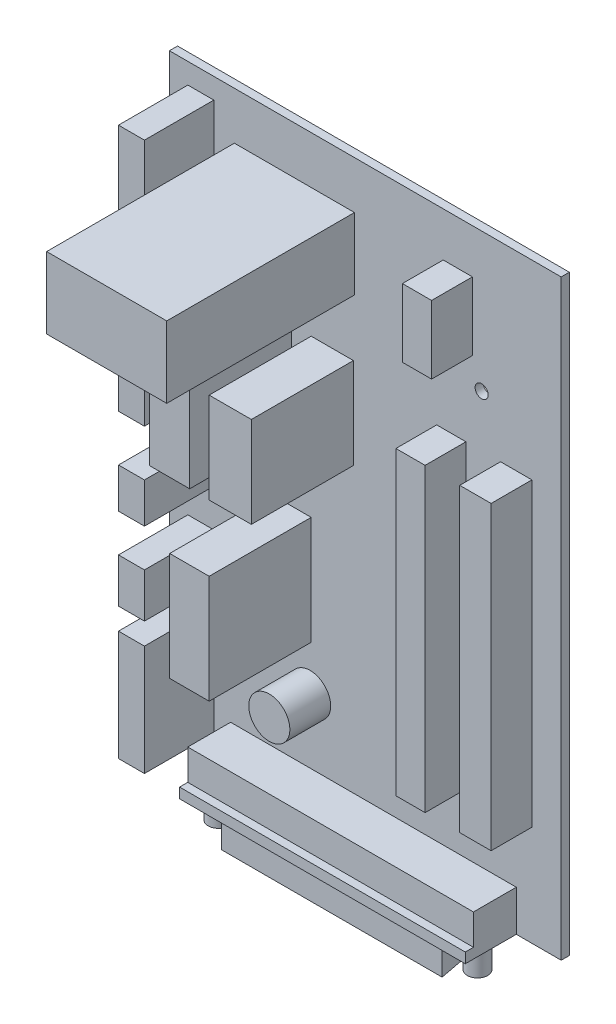
SolidWorks part; units mm, degrees
ref_plane "前视基准面" through (0, 0, 0) normal (0, 0, 1) x (1, 0, 0)
ref_plane "上视基准面" through (0, 0, 0) normal (0, 1, 0) x (1, 0, 0)
ref_plane "右视基准面" through (0, 0, 0) normal (1, 0, 0) x (0, 0, -1)
sketch "草图1" plane through (0, 0, 0) normal (0, 0, 1) x (1, 0, 0)
  line L0 (0, 0) -> (0, 68.734) construction
  line L1 (-48, 72.5) -> (48, 72.5)
  line L2 (-48, 72.5) -> (-48, -72.5)
  line L3 (-48, -72.5) -> (48, -72.5)
  line L4 (48, 72.5) -> (48, -72.5)
  line L5 (0, 0) -> (52.2466, 0) construction
  dimension "D1" = 96
  dimension "D2" = 145
extrude "凸台-拉伸1" add sketch "草图1" along normal blind 2
sketch "草图2" plane through (0, 0, 2) normal (0, 0, 1) x (1, 0, 0)
  line L1 (-43.4773, 67.4693) -> (-37.1147, 67.4693)
  line L2 (-43.4773, 67.4693) -> (-43.4773, 38.0426)
  line L3 (-43.4773, 38.0426) -> (-37.1147, 38.0426)
  line L4 (-37.1147, 67.4693) -> (-37.1147, 38.0426)
  line L5 (-43.4773, 29.5592) -> (-37.1147, 29.5592)
  line L6 (-43.4773, 29.5592) -> (-43.4773, 6.7602)
  line L7 (-43.4773, 6.7602) -> (-37.1147, 6.7602)
  line L8 (-37.1147, 29.5592) -> (-37.1147, 6.7602)
  line L9 (-43.4773, -4.6393) -> (-37.1147, -4.6393)
  line L10 (-43.4773, -4.6393) -> (-43.4773, -14.4482)
  line L11 (-43.4773, -14.4482) -> (-37.1147, -14.4482)
  line L12 (-37.1147, -4.6393) -> (-37.1147, -14.4482)
  line L13 (-43.4773, -23.7269) -> (-37.1147, -23.7269)
  line L14 (-43.4773, -23.7269) -> (-43.4773, -34.5962)
  line L15 (-43.4773, -34.5962) -> (-37.1147, -34.5962)
  line L16 (-37.1147, -23.7269) -> (-37.1147, -34.5962)
  line L17 (-43.4773, -39.8983) -> (-37.1147, -39.8983)
  line L18 (-43.4773, -39.8983) -> (-43.4773, -66.9391)
  line L19 (-43.4773, -66.9391) -> (-37.1147, -66.9391)
  line L20 (-37.1147, -39.8983) -> (-37.1147, -66.9391)
extrude "凸台-拉伸2" add sketch "草图2" along normal blind 17
sketch "草图3" plane through (0, 0, 2) normal (0, 0, 1) x (1, 0, 0)
  line L1 (-32.0777, 60.8417) -> (-2.6511, 60.8417)
  line L2 (-32.0777, 60.8417) -> (-32.0777, 43.3447)
  line L3 (-32.0777, 43.3447) -> (-2.6511, 43.3447)
  line L4 (-2.6511, 60.8417) -> (-2.6511, 43.3447)
extrude "凸台-拉伸3" add sketch "草图3" along normal blind 46
sketch "草图4" plane through (0, 0, 2) normal (0, 0, 1) x (1, 0, 0)
  line L1 (-27.8361, 29.2941) -> (-18.0272, 29.2941)
  line L2 (-27.8361, 29.2941) -> (-27.8361, 7.0253)
  line L3 (-27.8361, 7.0253) -> (-18.0272, 7.0253)
  line L4 (-18.0272, 29.2941) -> (-18.0272, 7.0253)
  line L5 (-13.2553, 29.2941) -> (-2.9162, 29.2941)
  line L6 (-13.2553, 29.2941) -> (-13.2553, 7.0253)
  line L7 (-13.2553, 7.0253) -> (-2.9162, 7.0253)
  line L8 (-2.9162, 29.2941) -> (-2.9162, 7.0253)
  line L9 (-22.9316, -9.1461) -> (-13.2553, -9.1461)
  line L10 (-22.9316, -9.1461) -> (-22.9316, -35.6567)
  line L11 (-22.9316, -35.6567) -> (-13.2553, -35.6567)
  line L12 (-13.2553, -9.1461) -> (-13.2553, -35.6567)
extrude "凸台-拉伸4" add sketch "草图4" along normal blind 25
sketch "草图5" plane through (0, 0, 2) normal (0, 0, 1) x (1, 0, 0)
  circle A0 centre (-13.5204, -46.7911) radius 5.037
extrude "凸台-拉伸5" add sketch "草图5" along normal blind 10
sketch "草图6" plane through (0, 0, 2) normal (0, 0, 1) x (1, 0, 0)
  line L1 (19.0876, 61.637) -> (26.2454, 61.637)
  line L2 (19.0876, 61.637) -> (19.0876, 44.9353)
  line L3 (19.0876, 44.9353) -> (26.2454, 44.9353)
  line L4 (26.2454, 61.637) -> (26.2454, 44.9353)
extrude "凸台-拉伸6" add sketch "草图6" along normal blind 10
sketch "草图7" plane through (0, 0, 2) normal (0, 0, 1) x (1, 0, 0)
  line L1 (17.4969, 25.8478) -> (24.6548, 25.8478)
  line L2 (17.4969, 25.8478) -> (17.4969, -47.8515)
  line L3 (17.4969, -47.8515) -> (24.6548, -47.8515)
  line L4 (24.6548, 25.8478) -> (24.6548, -47.8515)
  line L5 (33.1382, 25.8478) -> (40.8262, 25.8478)
  line L6 (33.1382, 25.8478) -> (33.1382, -47.8515)
  line L7 (33.1382, -47.8515) -> (40.8262, -47.8515)
  line L8 (40.8262, 25.8478) -> (40.8262, -47.8515)
extrude "凸台-拉伸7" add sketch "草图7" along normal blind 10
sketch "草图8" plane through (0, 0, 2) normal (0, 0, 1) x (1, 0, 0)
  line L0 (-48, 72.5) -> (-48, -72.5) construction
  line L1 (-48, -72.5) -> (48, -72.5) construction
  circle A0 centre (-31.5, -51.5) radius 1.6
  circle A1 centre (28.5, -51.5) radius 1.6
  circle A2 centre (-31.5, 38.5) radius 1.6
  circle A3 centre (28.5, 38.5) radius 1.6
  dimension "D3" = 3.2
  dimension "D1" = 16.5
  dimension "D2" = 21
  dimension "D4" = 60
  dimension "D5" = 90
extrude "切除-拉伸1" cut sketch "草图8" against normal through all
sketch "草图9" plane through (0, 0, 2) normal (0, 0, 1) x (1, 0, 0)
  line L0 (-48, -72.5) -> (48, -72.5) construction
  line L1 (-33, -72.5) -> (37, -72.5)
  line L2 (-33, -72.5) -> (-33, -62.5)
  line L3 (-33, -62.5) -> (37, -62.5)
  line L4 (37, -72.5) -> (37, -62.5)
  line L5 (48, -72.5) -> (48, 72.5) construction
  dimension "D1" = 11
  dimension "D2" = 70
  dimension "D3" = 10
extrude "凸台-拉伸8" add sketch "草图9" along normal blind 10.5
sketch "草图10" plane through (0, 0, 12.5) normal (0, 0, 1) x (1, 0, 0)
  line L0 (37, -72.5) -> (37, -62.5) construction
  line L1 (-33, -72.5) -> (37, -72.5)
  line L2 (-33, -72.5) -> (-33, -70)
  line L3 (-33, -70) -> (37, -70)
  line L4 (37, -72.5) -> (37, -70)
  dimension "D1" = 2.5
extrude "凸台-拉伸9" add sketch "草图10" along normal blind 2
sketch "草图11" plane through (0, -72.5, 0) normal (0, -1, 0) x (1, 0, 0)
  line L0 (-25, 12.175) -> (29, 12.175)
  line L1 (29, 12.175) -> (27.5, 4.325)
  line L2 (27.5, 4.325) -> (-23.5, 4.325)
  line L3 (-23.5, 4.325) -> (-25, 12.175)
  line L4 (2, 0) -> (2, 14.5) construction
  line L5 (-24.25, 8.25) -> (-8.5034, 8.25) construction
  line L6 (-33, 14.5) -> (37, 14.5) construction
  dimension "D1" = 7.85
  dimension "D2" = 6.25
  dimension "D3" = 54
  dimension "D4" = 51
extrude "凸台-拉伸10" add sketch "草图11" along normal blind 8
sketch "草图12" plane through (0, -72.5, 0) normal (0, -1, 0) x (1, 0, 0)
  line L0 (-33, 8.25) -> (-29.75, 8.25) construction
  line L1 (-33, 14.5) -> (-33, 2) construction
  line L2 (2, 14.5) -> (2, 5.6632) construction
  line L3 (-33, 14.5) -> (37, 14.5) construction
  circle A0 centre (-29.75, 8.25) radius 2.5
  circle A2 centre (33.75, 8.25) radius 2.5
  dimension "D2" = 5
  dimension "D1" = 63.5
extrude "凸台-拉伸11" add sketch "草图12" along normal blind 6
hole_wizard "M3x0.5 螺纹孔1" positions "草图14" profile "草图13" tap size "M3x0.5" standard "JIS"
sketch "草图14" plane through (0, -78.5, 0) normal (0, -1, 0) x (1, 0, 0)
  point P1 (-29.75, 8.25)
  point P4 (33.75, 8.25)
sketch "草图13" plane through (-29.75, -78.5, 8.25) normal (1, 0, 0) x (0, 0, -1)
  line L0 (0, 0) -> (0, 8.2511)
  line L1 (0, 8.2511) -> (1.25, 7.5)
  line L2 (1.25, 7.5) -> (1.25, 0)
  line L5 (1.25, 0) -> (0, 0)
  line L10 (0, 8.2511) -> (-1.25, 7.5) construction
  line L11 (0, -6.35) -> (0, 107.95) construction
  dimension "螺纹孔钻头直径" = 2.5
  dimension "螺纹孔钻头深度" = 7.5
  dimension "导头角度" = 118
cosmetic thread "孔螺蚊线1" parameters "D1"=6, "D2"=3
cosmetic thread "孔螺蚊线2" parameters "D1"=6, "D2"=3
